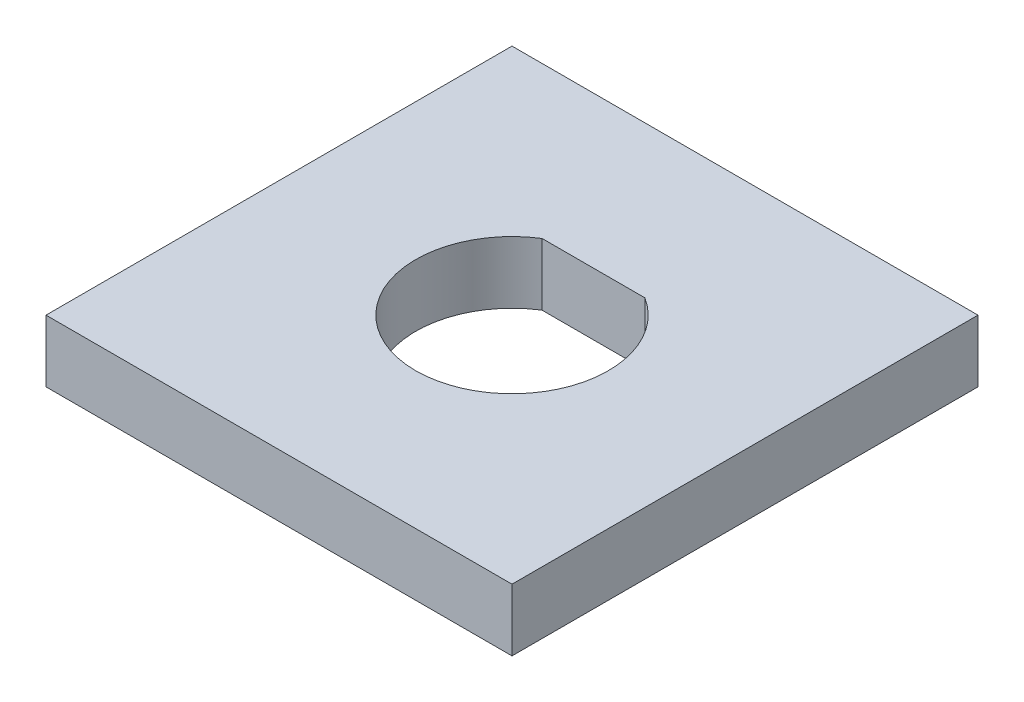
SolidWorks part; units mm, degrees
ref_plane "Front Plane" through (0, 0, 0) normal (0, 0, 1) x (1, 0, 0)
ref_plane "Top Plane" through (0, 0, 0) normal (0, 1, 0) x (1, 0, 0)
ref_plane "Right Plane" through (0, 0, 0) normal (1, 0, 0) x (0, 0, -1)
sketch "Sketch1" plane through (0, 0, 0) normal (0, 1, 0) x (1, 0, 0)
  line L0 (-1.655, 2.6213) -> (1.655, 2.6213)
  line L1 (-7.5, -7.5) -> (7.5, -7.5)
  line L2 (-7.5, -7.5) -> (-7.5, 7.5)
  line L3 (-7.5, 7.5) -> (7.5, 7.5)
  line L4 (7.5, -7.5) -> (7.5, 7.5)
  line L5 (-7.5, -7.5) -> (2.192, 2.192) construction
  line L6 (-7.5, 7.5) -> (7.5, -7.5) construction
  arc A0 (-1.655, 2.6213) -> (1.655, 2.6213) centre (0, 0) ccw
  point P0 (0, 0)
  dimension "D3" = 6.2
  dimension "D1" = 15
  dimension "D2" = 15
  dimension "D4" = 3.31
extrude "Boss-Extrude1" add sketch "Sketch1" along normal blind 2
